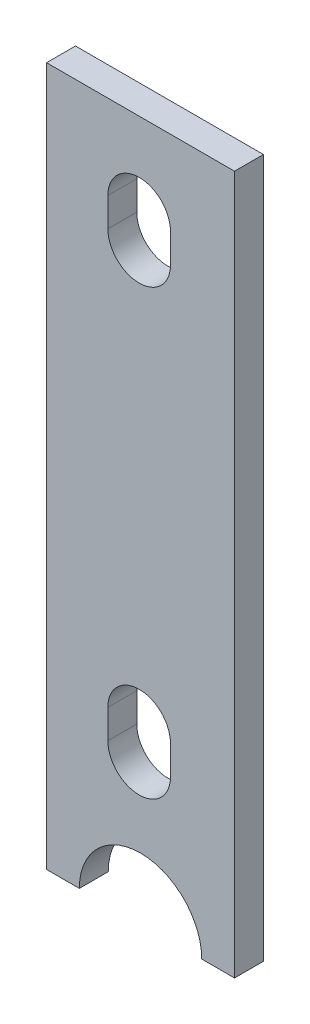
SolidWorks part; units mm, degrees
ref_plane "Front Plane" through (0, 0, 0) normal (0, 0, 1) x (1, 0, 0)
ref_plane "Top Plane" through (0, 0, 0) normal (0, 1, 0) x (1, 0, 0)
ref_plane "Right Plane" through (0, 0, 0) normal (1, 0, 0) x (0, 0, -1)
sketch "Sketch1" plane through (0, 0, 0) normal (0, 0, 1) x (1, 0, 0)
  line L1 (0, 0) -> (39, 0)
  line L2 (0, 0) -> (0, -145)
  line L3 (0, -145) -> (39, -145)
  line L4 (39, 0) -> (39, -145)
  dimension "D1" = 145
  dimension "D2" = 39
extrude "Boss-Extrude1" add sketch "Sketch1" along normal blind 6
sketch "Sketch4" plane through (0, 0, 6) normal (0, 0, 1) x (1, 0, 0)
  line L8 (19.2173, -109.5) -> (19.2173, -115.5) construction
  line L9 (25.7173, -109.5) -> (25.7173, -115.5)
  line L10 (12.7173, -109.5) -> (12.7173, -115.5)
  line L11 (19.2173, -23.5) -> (19.2173, -17.5) construction
  line L12 (25.7173, -23.5) -> (25.7173, -17.5)
  line L13 (12.7173, -23.5) -> (12.7173, -17.5)
  arc A0 (25.7173, -109.5) -> (12.7173, -109.5) centre (19.2173, -109.5) ccw
  arc A1 (12.7173, -115.5) -> (25.7173, -115.5) centre (19.2173, -115.5) ccw
  arc A2 (25.7173, -23.5) -> (12.7173, -23.5) centre (19.2173, -23.5) cw
  arc A3 (12.7173, -17.5) -> (25.7173, -17.5) centre (19.2173, -17.5) cw
  point P14 (19.2173, -112.5)
  point P21 (19.2173, -20.5)
  dimension "D4" = 6.5
  dimension "D3" = 6
  dimension "D5" = 92
extrude "Cut-Extrude2" cut sketch "Sketch4" against normal blind 6
sketch "Sketch5" plane through (0, 0, 6) normal (0, 0, 1) x (1, 0, 0)
  line L0 (0, -145) -> (39, -145) construction
  line L1 (6.8, -145) -> (32.2, -145)
  arc A0 (6.8, -145) -> (32.2, -145) centre (19.5, -145) cw
  point P3 (19.5, -145)
  dimension "D1" = 12.7
extrude "Cut-Extrude3" cut sketch "Sketch5" against normal blind 10
